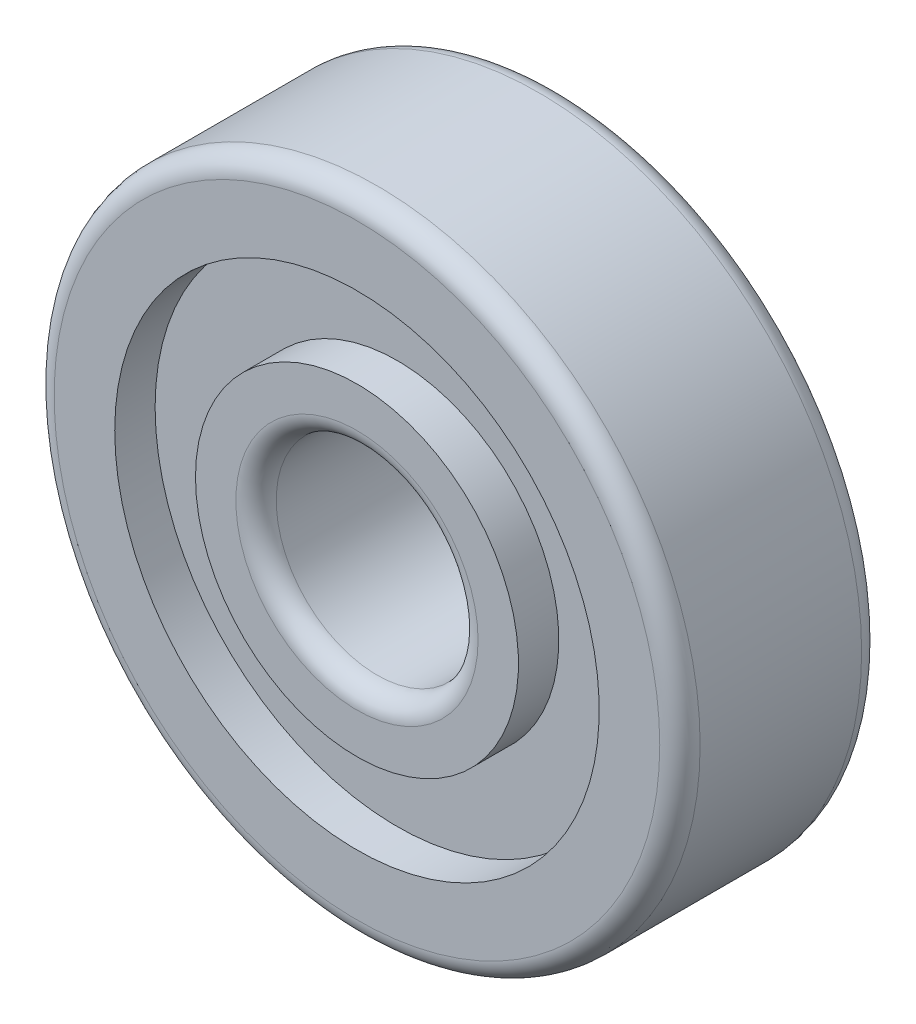
SolidWorks part; units mm, degrees
ref_plane "前基準面" through (0, 0, 0) normal (0, 0, 1) x (1, 0, 0)
ref_plane "上基準面" through (0, 0, 0) normal (0, 1, 0) x (1, 0, 0)
ref_plane "右基準面" through (0, 0, 0) normal (1, 0, 0) x (0, 0, -1)
sketch "草圖3" plane through (0, 0, 0) normal (0, 0, 1) x (1, 0, 0)
  circle A0 centre (0, 0) radius 8
  circle A1 centre (0, 0) radius 2.5
  dimension "D1" = 16
  dimension "D2" = 5
extrude "填料-伸長1" add sketch "草圖3" along normal mid plane 5
fillet "圓角1" radius 0.5 4 edges at (2.5, 0, -2.5) (2.5, 0, 2.5) (8, 0, -2.5) (8, 0, 2.5)
sketch "草圖4" plane through (0, 0, -2.5) normal (0, 0, -1) x (-1, 0, 0)
  circle A0 centre (0, 0) radius 4
  circle A2 centre (0, 0) radius 6
  dimension "D1" = 8
  dimension "D2" = 12
extrude "除料-伸長1" cut sketch "草圖4" against normal blind 1
mirror "鏡射1" about plane through (0, 0, 0) normal (0, 0, 1) of "除料-伸長1"
